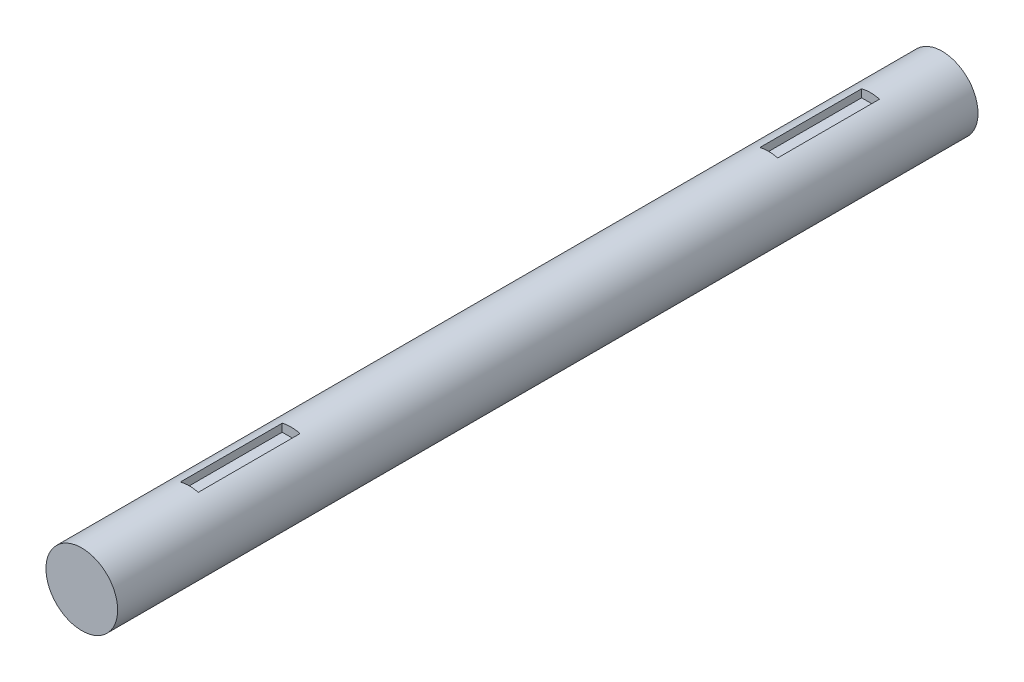
SolidWorks part; units mm, degrees
ref_plane "Front Plane" through (0, 0, 0) normal (0, 0, 1) x (1, 0, 0)
ref_plane "Top Plane" through (0, 0, 0) normal (0, 1, 0) x (1, 0, 0)
ref_plane "Right Plane" through (0, 0, 0) normal (1, 0, 0) x (0, 0, -1)
sketch "Sketch1" plane through (0, 0, 0) normal (0, 0, 1) x (1, 0, 0)
  circle A0 centre (0, 0) radius 6.35
  dimension "D1" = 12.7
extrude "Boss-Extrude1" add sketch "Sketch1" along normal blind 152.4
ref_plane "Plane1" through (0, 0, 12.7) normal (0, 0, -1) x (-1, 0, 0)
sketch "Sketch2" plane through (0, 0, 12.7) normal (0, 0, -1) x (-1, 0, 0)
  line L0 (1.5714, 4.7625) -> (-0.0161, 4.7625)
  line L1 (0, 0) -> (0, 6.35) construction
  line L2 (1.5714, 4.7625) -> (1.5714, 7.9375)
  line L3 (1.5714, 7.9375) -> (-1.6036, 7.9375)
  line L4 (-1.6036, 7.9375) -> (-1.6036, 4.7625)
  line L5 (-0.0161, 4.7625) -> (-1.6036, 4.7625)
  circle A1 centre (0, 0) radius 6.35 construction
  dimension "D1" = 1.5875
  dimension "D2" = 1.5875
  dimension "D3" = 1.5875
  dimension "D4" = 3.175
extrude "Cut-Extrude1" cut sketch "Sketch2" against normal blind 18.034
ref_plane "Plane2" through (0, 0, 133.35) normal (0, 0, 1) x (1, 0, 0)
sketch "Sketch3" plane through (0, 0, 133.35) normal (0, 0, 1) x (1, 0, 0)
  line L0 (0, 6.35) -> (0, 4.7625)
  line L1 (0, 4.7625) -> (1.5875, 4.7625)
  line L2 (1.5875, 4.7625) -> (1.5875, 7.9375)
  line L3 (1.5875, 7.9375) -> (-1.5875, 7.9375)
  line L4 (-1.5875, 7.9375) -> (-1.5875, 4.7625)
  line L5 (-1.5875, 4.7625) -> (0, 4.7625)
  circle A0 centre (0, 0) radius 6.35 construction
  dimension "D1" = 1.5875
  dimension "D2" = 1.5875
  dimension "D3" = 3.175
  dimension "D4" = 1.5875
extrude "Cut-Extrude2" cut sketch "Sketch3" against normal blind 18.034
